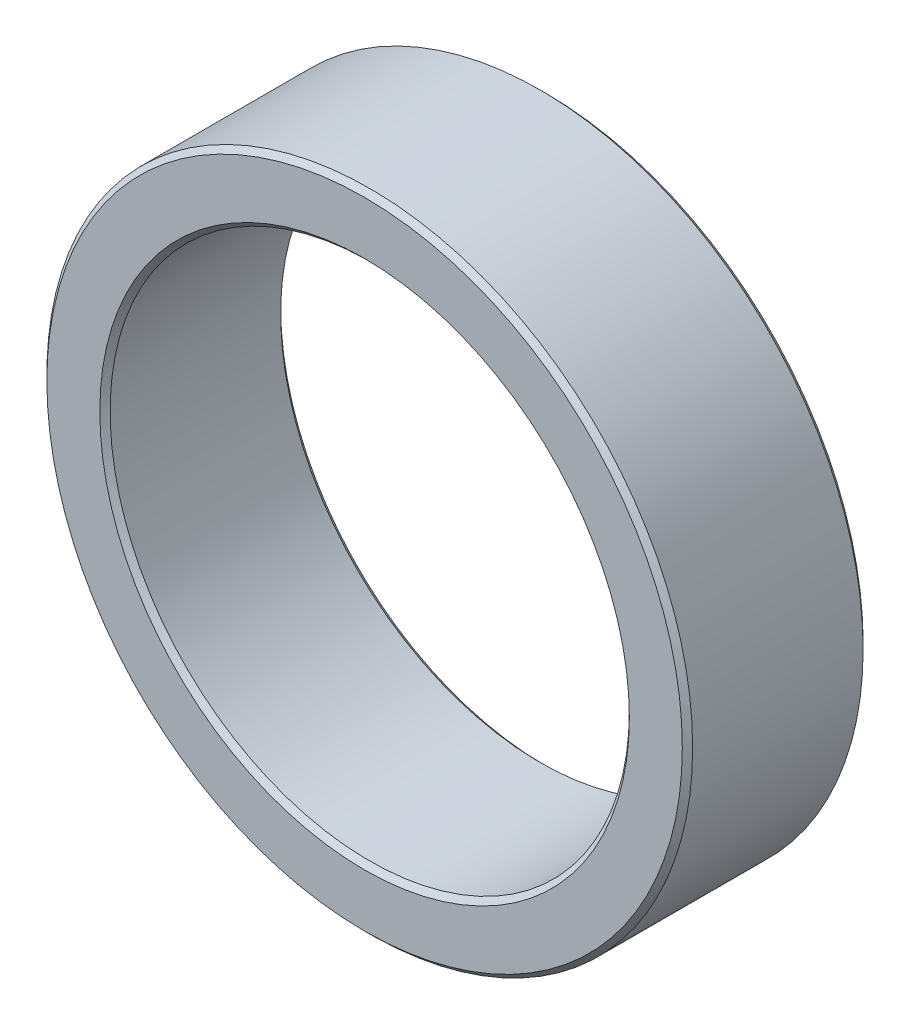
SolidWorks part; units mm, degrees
material "316 Stainless Steel"
ref_plane "Front Plane" through (0, 0, 0) normal (0, 0, 1) x (1, 0, 0)
ref_plane "Top Plane" through (0, 0, 0) normal (0, 1, 0) x (1, 0, 0)
ref_plane "Right Plane" through (0, 0, 0) normal (1, 0, 0) x (0, 0, -1)
sketch "Sketch1" plane through (0, 0, 0) normal (0, 0, 1) x (1, 0, 0)
  circle A0 centre (0, 0) radius 12.5
  circle A1 centre (0, 0) radius 10.05
  dimension "D1" = 20.1
  dimension "D2" = 25
extrude "Boss-Extrude1" add sketch "Sketch1" along normal blind 7
chamfer "Chamfer1" distance 0.2 angle 45 4 edges at (12.5, 0, 0) (12.5, 0, 7) (10.05, 0, 0) (10.05, 0, 7)
